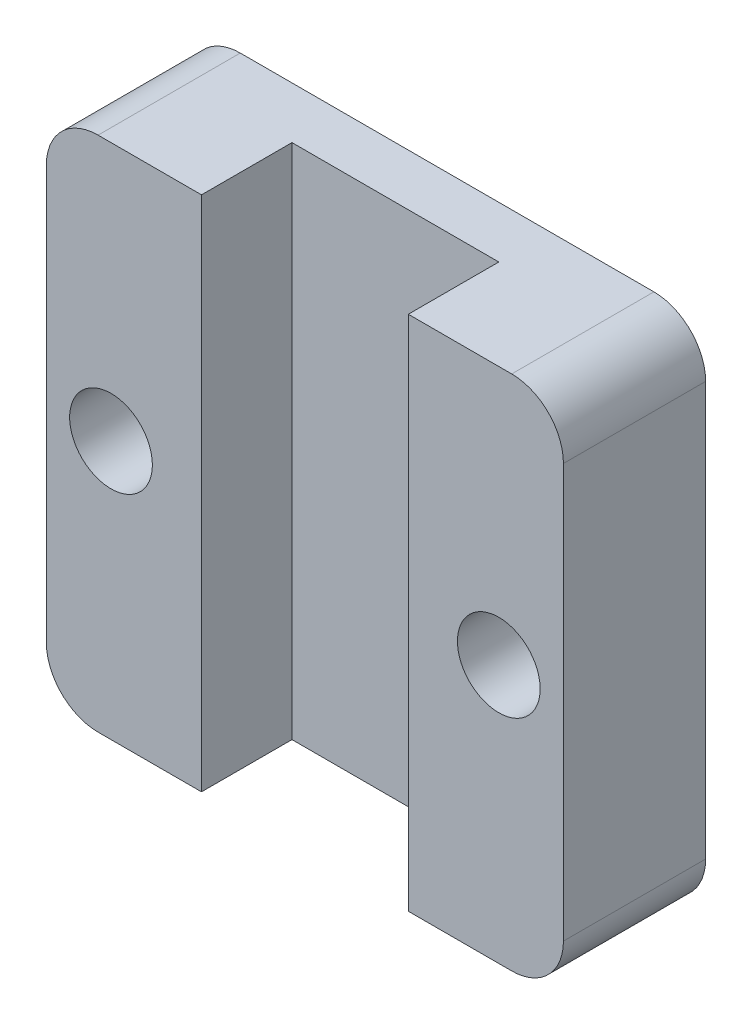
SolidWorks part; units mm, degrees
ref_plane "Front Plane" through (0, 0, 0) normal (0, 0, 1) x (1, 0, 0)
ref_plane "Top Plane" through (0, 0, 0) normal (0, 1, 0) x (1, 0, 0)
ref_plane "Right Plane" through (0, 0, 0) normal (1, 0, 0) x (0, 0, -1)
ref_plane "Plane4" through (0, 0, 0) normal (0, 0, -1) x (-1, 0, 0)
sketch "Sketch1" plane through (0, 0, 0) normal (0, 0, -1) x (-1, 0, 0)
  line L0 (10, 10) -> (-10, 10)
  line L1 (-10, 10) -> (-10, -10)
  line L2 (-10, -10) -> (10, -10)
  line L3 (10, -10) -> (10, 10)
  dimension "D1" = 10
  dimension "D2" = 10
  dimension "D3" = 10
extrude "Boss-Extrude1" add sketch "Sketch1" against normal blind 5.5
sketch "Sketch2" plane through (0, 10, 0) normal (0, 1, 0) x (-1, 0, 0)
  line L0 (4, 5.5) -> (-4, 5.5)
  line L1 (-4, 5.5) -> (-4, 2)
  line L2 (-4, 2) -> (4, 2)
  line L3 (4, 2) -> (4, 5.5)
  dimension "D1" = 4
  dimension "D2" = 4
  dimension "D3" = 2
  dimension "D4" = 5.5
extrude "Cut-Extrude1" cut sketch "Sketch2" against normal through all
hole_wizard "HoleWzd1" positions "Sketch4" profile "Sketch3" hole size "Ø3.2" standard "ANSI Metric"
sketch "Sketch4" plane through (0, 0, 5.5) normal (0, 0, 1) x (1, 0, 0)
  point P0 (7.5, 0)
  point P1 (-7.5, 0)
sketch "Sketch3" plane through (7.5, 0, 5.5) normal (1, 0, 0) x (0, -1, 0)
  line L0 (0, 0) -> (0, 5.5)
  line L1 (0, 5.5) -> (1.6, 5.5)
  line L2 (1.6, 5.5) -> (1.6, 0)
  line L5 (1.6, 0) -> (0, 0)
  line L11 (0, -6.35) -> (0, 107.95) construction
  dimension "通孔孔直径" = 3.2
  dimension "通孔孔深度" = 5.5
fillet "Fillet1" radius 2 4 edges at (-10, 10, 2.75) (-10, -10, 2.75) (10, 10, 2.75) (10, -10, 2.75)
